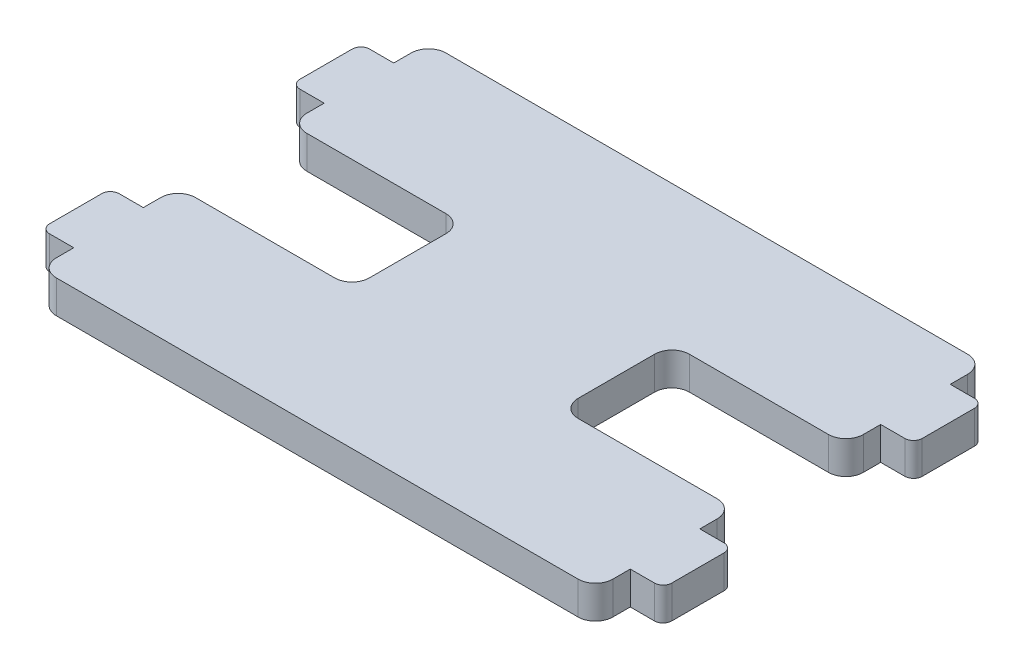
SolidWorks part; units mm, degrees
ref_plane "Front Plane" through (0, 0, 0) normal (0, 0, 1) x (1, 0, 0)
ref_plane "Top Plane" through (0, 0, 0) normal (0, 1, 0) x (1, 0, 0)
ref_plane "Right Plane" through (0, 0, 0) normal (1, 0, 0) x (0, 0, -1)
sketch "Sketch1" plane through (0, 0, 0) normal (0, 1, 0) x (1, 0, 0)
  line L0 (25.4, 5.08) -> (9.525, 5.08)
  line L1 (-25.4, -17.78) -> (-12.458, -17.78)
  line L2 (-25.4, -17.78) -> (-25.4, -5.08)
  line L4 (25.4, -17.78) -> (25.4, -5.08)
  line L5 (-25.4, -17.78) -> (25.4, 17.78) construction
  line L6 (-25.4, 17.78) -> (25.4, -17.78) construction
  line L7 (9.525, 5.08) -> (9.525, -5.08)
  line L8 (9.525, -5.08) -> (25.4, -5.08)
  line L9 (-25.4, -5.08) -> (-9.525, -5.08)
  line L10 (-9.525, -5.08) -> (-9.525, 5.08)
  line L11 (-9.525, 5.08) -> (-25.4, 5.08)
  line L12 (0, -17.78) -> (0, 17.78) construction
  line L13 (-25.4, -5.08) -> (-25.4, 5.08) construction
  line L14 (-25.4, 5.08) -> (-25.4, 17.78)
  line L15 (25.4, -5.08) -> (25.4, 5.08) construction
  line L16 (25.4, 5.08) -> (25.4, 17.78)
  line L20 (0, -17.78) -> (6.592, -17.78)
  line L21 (6.592, -17.78) -> (25.4, -17.78)
  line L22 (-12.458, -17.78) -> (0, -17.78)
  line L27 (-25.4, 17.78) -> (25.4, 17.78)
  point P0 (0, 0)
  dimension "D1" = 50.8
  dimension "D2" = 35.56
  dimension "D3" = 12.7
  dimension "D4" = 12.7
  dimension "D5" = 19.05
extrude "Boss-Extrude1" add sketch "Sketch1" along normal mid plane 3
fillet "Fillet1" radius 1.5875 12 edges at (25.4, 0, -5.08) (9.525, 0, -5.08) (9.525, 0, 5.08) (25.4, 0, 5.08) (25.4, 0, 17.78) (-25.4, 0, 5.08) (-9.525, 0, 5.08) (-9.525, 0, -5.08) (-25.4, 0, -5.08) (-25.4, 0, 17.78) (25.4, 0, -17.78) (-25.4, 0, -17.78)
sketch "Sketch2" plane through (0, 1.5, 0) normal (0, 1, 0) x (1, 0, 0)
  line L0 (-26.9, 11.43) -> (-26.9, -11.43) construction
  line L5 (-25.4, 5.08) -> (-25.4, 17.78) construction
  line L6 (-26.9, 0) -> (0, 0) construction
  line L12 (-25.4, -17.78) -> (-25.4, -5.08) construction
  line L13 (25.4, 5.08) -> (25.4, 17.78) construction
  line L14 (25.4, -17.78) -> (25.4, -5.08) construction
  line B0 (-28.4, 8.255) -> (-25.4, 8.255)
  line B1 (-28.4, 8.255) -> (-28.4, 14.605)
  line B2 (-28.4, 14.605) -> (-25.4, 14.605)
  line B3 (-25.4, 8.255) -> (-25.4, 14.605)
  line B4 (-28.4, 8.255) -> (-25.4, 14.605) construction
  line B5 (-28.4, 14.605) -> (-25.4, 8.255) construction
  line B6 (25.4, 8.255) -> (28.4, 8.255)
  line B7 (25.4, 8.255) -> (25.4, 14.605)
  line B8 (25.4, 14.605) -> (28.4, 14.605)
  line B9 (28.4, 8.255) -> (28.4, 14.605)
  line B10 (25.4, -14.605) -> (28.4, -14.605)
  line B11 (25.4, -14.605) -> (25.4, -8.255)
  line B12 (25.4, -8.255) -> (28.4, -8.255)
  line B13 (28.4, -14.605) -> (28.4, -8.255)
  line B14 (-28.4, -14.605) -> (-25.4, -14.605)
  line B15 (-28.4, -14.605) -> (-28.4, -8.255)
  line B16 (-28.4, -8.255) -> (-25.4, -8.255)
  line B17 (-25.4, -14.605) -> (-25.4, -8.255)
  dimension "D1" = 22.86
sketch_block_instance "Block1-1"
sketch_block "Block1" parameters "D1"=6.35, "D2"=3
sketch_block_instance "Block1-2"
sketch_block_instance "Block1-3"
sketch_block_instance "Block1-4"
extrude "Boss-Extrude2" add sketch "Sketch2" against normal up to surface (3 mm away) up to face at (0, -1.5, 0)
fillet "Fillet2" radius 0.7937 8 edges at (-28.4, 0, 14.605) (-28.4, 0, 8.255) (28.4, 0, 8.255) (28.4, 0, 14.605) (28.4, 0, -14.605) (28.4, 0, -8.255) (-28.4, 0, -14.605) (-28.4, 0, -8.255)
